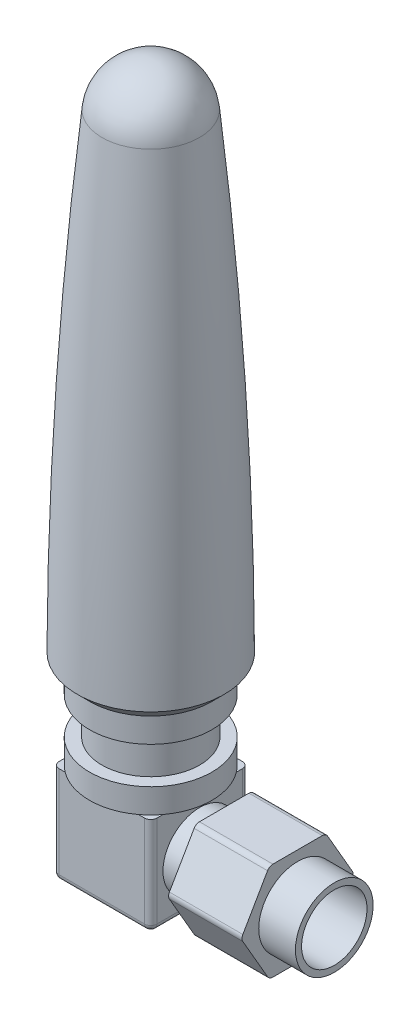
SolidWorks part; units mm, degrees
ref_plane "前视基准面" through (0, 0, 0) normal (0, 0, 1) x (1, 0, 0)
ref_plane "上视基准面" through (0, 0, 0) normal (0, 1, 0) x (1, 0, 0)
ref_plane "右视基准面" through (0, 0, 0) normal (1, 0, 0) x (0, 0, -1)
sketch "草图1" plane through (0, 0, 0) normal (0, 0, 1) x (1, 0, 0)
  line L0 (0, -56.2212) -> (0, 56.2212) construction
  line L1 (0, 0) -> (5, 0)
  line L2 (5, 0) -> (5, 2)
  line L3 (5, 2) -> (4, 2)
  line L4 (4, 2) -> (4, 5)
  line L5 (4, 5) -> (5, 5)
  line L6 (5, 5) -> (5, 7)
  line L7 (5, 7) -> (6, 8)
  line L8 (0, 50) -> (-9.4771, 50) construction
  line L9 (0, 50) -> (0, 0)
  arc A0 (6, 8) -> (3.9798, 46.4019) centre (-393.996, 6.2112) ccw
  arc A1 (3.9798, 46.4019) -> (0, 50) centre (0, 46) ccw
  point P4 (0, 0)
  dimension "D8" = 400
  dimension "D9" = 4
  dimension "D1" = 2
  dimension "D2" = 3
  dimension "D3" = 2
  dimension "D4" = 1
  dimension "D5" = 10
  dimension "D6" = 1
  dimension "D7" = 1
  dimension "D10" = 50
revolve "旋转1" add sketch "草图1" angle 360 about L0
sketch "草图2" plane through (0, 0, 0) normal (0, -1, 0) x (1, 0, 0)
  line L1 (-4, -4) -> (4, -4)
  line L2 (-4, -4) -> (-4, 4)
  line L3 (-4, 4) -> (4, 4)
  line L4 (4, -4) -> (4, 4)
  line L5 (-4, -4) -> (4, 4) construction
  line L6 (-4, 4) -> (4, -4) construction
  point P0 (0, 0)
  dimension "D1" = 8
extrude "凸台-拉伸1" add sketch "草图2" along normal blind 8
sketch "草图3" plane through (0, 0, 0) normal (0, 0, 1) x (1, 0, 0)
  line L0 (-4, -4) -> (27.6057, -4) construction
  line L1 (-4, -8) -> (-4, 0) construction
  line L2 (4, -4) -> (4, -1)
  line L3 (4, -8) -> (4, 0) construction
  line L4 (4, -1) -> (6, -1)
  line L5 (6, 1) -> (12, 1)
  line L6 (12, 1) -> (12, -0.825)
  line L7 (12, -0.825) -> (15, -0.825)
  line L8 (6, 1) -> (6, -1)
  line L9 (15, -0.825) -> (15, -1.325)
  line L10 (15, -1.325) -> (7, -1.325)
  line L11 (7, -1.325) -> (7, -3.6)
  line L12 (7, -3.6) -> (12, -3.6)
  line L14 (12.4, -4) -> (4, -4)
  arc A0 (12, -3.6) -> (12.4, -4) centre (12, -4) cw
  point P14 (0, 0)
  point P21 (0, 0)
  point P22 (0, 0)
  point P23 (16.3708, -3)
  dimension "D1" = 2
  dimension "D2" = 6
  dimension "D3" = 10
  dimension "D4" = 6.35
  dimension "D5" = 6
  dimension "D6" = 3
  dimension "D7" = 8
  dimension "D8" = 0.5
  dimension "D9" = 0.8
  dimension "D10" = 5
revolve "旋转2" add sketch "草图3" angle 360 about L0
sketch "草图4" plane through (12, 0, 0) normal (1, 0, 0) x (0, 0, -1)
  line L1 (2.3094, 0) -> (-2.3094, 0)
  line L2 (-2.3094, 0) -> (-4.6188, -4)
  line L3 (-4.6188, -4) -> (-2.3094, -8)
  line L4 (-2.3094, -8) -> (2.3094, -8)
  line L5 (2.3094, -8) -> (4.6188, -4)
  line L6 (4.6188, -4) -> (2.3094, 0)
  circle A0 centre (0, -4) radius 4 construction
  circle A3 centre (0, -4) radius 5
  dimension "D1" = 8
extrude "切除-拉伸1" cut sketch "草图4" against normal up to surface (6 mm away) up to face at (6, -4, 3)
fillet "圆角1" radius 0.5 14 edges at (9, 0, -2.3094) (9, -4, -4.6188) (9, -8, -2.3094) (9, -8, 2.3094) (9, -4, 4.6188) (9, 0, 2.3094) (4, -4, -4) (4, -8, 0) (0, -8, -4) (-4, -4, -4) (-4, -8, 0) (4, -4, 4) (-4, -4, 4) (0, -8, 4)
